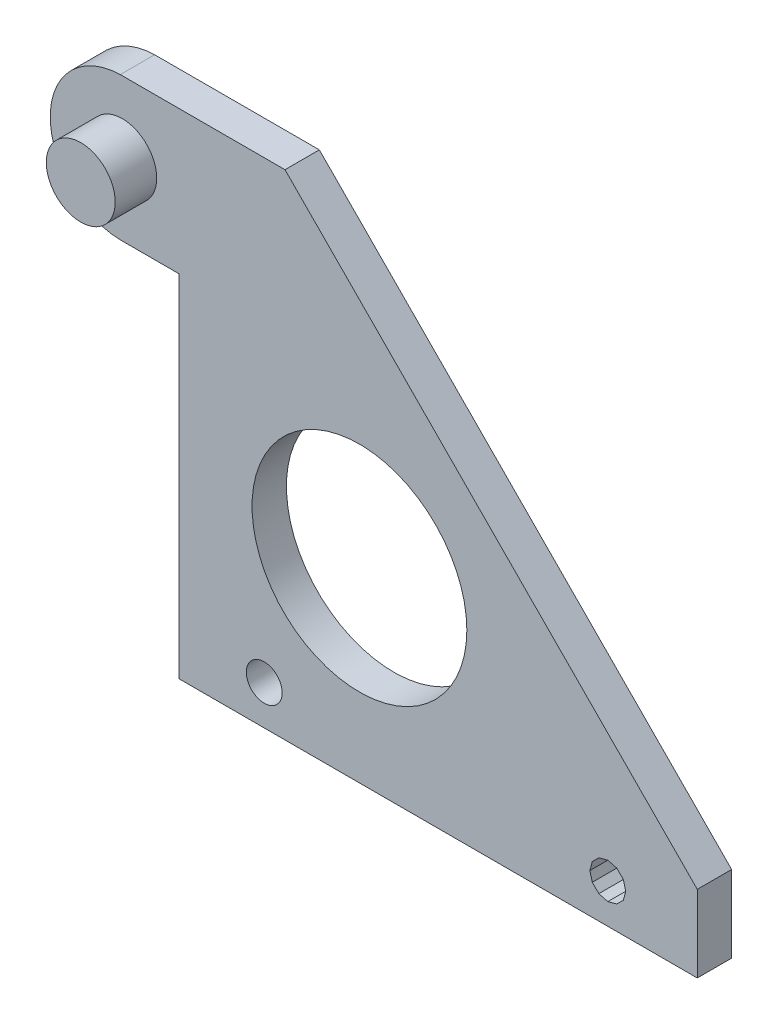
SolidWorks part; units mm, degrees
material "ABS"
ref_plane "Plan de face" through (0, 0, 0) normal (0, 0, 1) x (1, 0, 0)
ref_plane "Plan de dessus" through (0, 0, 0) normal (0, 1, 0) x (1, 0, 0)
ref_plane "Plan de droite" through (0, 0, 0) normal (1, 0, 0) x (0, 0, -1)
ref_plane "Plan1" through (0, 0, 2.4) normal (0, 0, 1) x (1, 0, 0)
sketch "Esquisse4" plane through (0, 0, 2.4) normal (0, 0, 1) x (1, 0, 0)
  line L0 (-20.1, -24.6348) -> (-48.9004, 4.5)
  line L1 (-48.9004, 4.5) -> (-60.4056, 4.5)
  line L2 (-60.4056, 4.5) -> (-61.692, 4.331) construction
  line L3 (-61.692, 4.331) -> (-62.899, 3.831) construction
  line L4 (-62.899, 3.831) -> (-63.935, 3.037) construction
  line L5 (-63.935, 3.037) -> (-64.73, 2.001) construction
  line L6 (-64.73, 2.001) -> (-65.3, 0.625) construction
  line L7 (-65.3, 0.625) -> (-65.3, -1.625) construction
  line L8 (-65.3, -1.625) -> (-64.73, -3.001) construction
  line L9 (-64.73, -3.001) -> (-63.935, -4.037) construction
  line L10 (-63.935, -4.037) -> (-62.899, -4.831) construction
  line L11 (-62.899, -4.831) -> (-61.692, -5.331) construction
  line L12 (-61.692, -5.331) -> (-60.4056, -5.5) construction
  line L13 (-60.4056, -5.5) -> (-56.3, -5.5)
  line L14 (-56.3, -5.5) -> (-56.3, -24.6348)
  line L15 (-56.3, -24.6348) -> (-20.1, -24.6348)
  arc A0 (-60.4056, 4.5) -> (-60.4056, -5.5) centre (-60.2989, -0.5) ccw
extrude "Boss.-Extru.1" add sketch "Esquisse4" against normal blind 2.4
ref_plane "Plan2" through (0, -24.6348, 0) normal (0, -1, 0) x (-1, 0, 0)
sketch "Esquisse9" plane through (0, -24.6348, 0) normal (0, -1, 0) x (-1, 0, 0)
  line L0 (56.3, -2.4) -> (20.1, -2.4)
  line L1 (20.1, -2.4) -> (20.1, 0)
  line L2 (20.1, 0) -> (56.3, 0)
  line L3 (56.3, 0) -> (56.3, -2.4)
extrude "Boss.-Extru.2" add sketch "Esquisse9" along normal blind 5.3652
sketch "Esquisse14" plane through (0, 0, 2.4) normal (0, 0, 1) x (1, 0, 0)
  line L0 (-38.395, -22.305) -> (-37.462, -21.168) construction
  line L1 (-37.462, -21.168) -> (-36.769, -19.871) construction
  line L2 (-36.769, -19.871) -> (-36.342, -18.464) construction
  line L3 (-36.342, -18.464) -> (-36.198, -17) construction
  line L4 (-36.198, -17) -> (-36.7804, -14.9449) construction
  line L5 (-36.7804, -14.9449) -> (-37.2074, -13.5379) construction
  line L6 (-37.2074, -13.5379) -> (-37.9004, -12.2409) construction
  line L7 (-37.9004, -12.2409) -> (-38.3671, -11.6721) construction
  line L8 (-38.3671, -11.6721) -> (-39.532, -10.762) construction
  line L9 (-39.532, -10.762) -> (-40.829, -10.069) construction
  line L10 (-40.829, -10.069) -> (-42.236, -9.642) construction
  line L11 (-42.236, -9.642) -> (-43.7, -9.498) construction
  line L12 (-43.7, -9.498) -> (-45.164, -9.642) construction
  line L13 (-45.164, -9.642) -> (-46.571, -10.069) construction
  line L14 (-46.571, -10.069) -> (-47.868, -10.762) construction
  line L15 (-47.868, -10.762) -> (-49.005, -11.695) construction
  line L16 (-49.005, -11.695) -> (-49.938, -12.832) construction
  line L17 (-49.938, -12.832) -> (-50.631, -14.129) construction
  line L18 (-50.631, -14.129) -> (-51.058, -15.536) construction
  line L19 (-51.058, -15.536) -> (-51.203, -17) construction
  line L20 (-51.203, -17) -> (-51.058, -18.464) construction
  line L21 (-51.058, -18.464) -> (-50.631, -19.871) construction
  line L22 (-50.631, -19.871) -> (-49.938, -21.168) construction
  line L23 (-49.938, -21.168) -> (-49.005, -22.305) construction
  line L24 (-49.005, -22.305) -> (-47.868, -23.238) construction
  line L25 (-47.868, -23.238) -> (-46.571, -23.931) construction
  line L26 (-46.571, -23.931) -> (-45.164, -24.358) construction
  line L27 (-45.164, -24.358) -> (-43.7, -24.502) construction
  line L28 (-43.7, -24.502) -> (-42.236, -24.358) construction
  line L29 (-42.236, -24.358) -> (-40.829, -23.931) construction
  line L30 (-40.829, -23.931) -> (-39.532, -23.238) construction
  line L31 (-39.532, -23.238) -> (-38.395, -22.305) construction
  circle A0 centre (-43.7, -16.9999) radius 7.5023
extrude "Enlèv. mat.-Extru.1" cut sketch "Esquisse14" against normal through all
sketch "Esquisse19" plane through (0, 0, 2.4) normal (0, 0, 1) x (1, 0, 0)
  line L0 (-26.35, -28.503) -> (-25.724, -28.335)
  line L1 (-25.724, -28.335) -> (-25.265, -27.876)
  line L2 (-25.265, -27.876) -> (-25.097, -27.25)
  line L3 (-25.097, -27.25) -> (-25.265, -26.624)
  line L4 (-25.265, -26.624) -> (-25.724, -26.165)
  line L5 (-25.724, -26.165) -> (-26.35, -25.998)
  line L6 (-26.35, -25.998) -> (-26.976, -26.165)
  line L7 (-26.976, -26.165) -> (-27.435, -26.624)
  line L8 (-27.435, -26.624) -> (-27.602, -27.25)
  line L9 (-27.602, -27.25) -> (-27.435, -27.876)
  line L10 (-27.435, -27.876) -> (-26.976, -28.335)
  line L11 (-26.976, -28.335) -> (-26.35, -28.503)
extrude "Enlèv. mat.-Extru.2" cut sketch "Esquisse19" against normal through all
ref_plane "Plan3" through (0, 0, 0) normal (0, 0, -1) x (-1, 0, 0)
sketch "Esquisse25" plane through (0, 0, 0) normal (0, 0, -1) x (-1, 0, 0)
  line L0 (49.265, -26.624) -> (49.097, -27.25) construction
  line L1 (49.097, -27.25) -> (49.265, -27.876) construction
  line L2 (49.265, -27.876) -> (49.724, -28.335) construction
  line L3 (49.724, -28.335) -> (50.35, -28.503) construction
  line L4 (50.35, -28.503) -> (50.976, -28.335) construction
  line L5 (50.976, -28.335) -> (51.435, -27.876) construction
  line L6 (51.435, -27.876) -> (51.602, -27.25) construction
  line L7 (51.602, -27.25) -> (51.2358, -26.3644) construction
  line L8 (51.2358, -26.3644) -> (51.0062, -26.1348) construction
  line L9 (51.0062, -26.1348) -> (50.35, -25.998) construction
  line L10 (50.35, -25.998) -> (49.724, -26.165) construction
  line L11 (49.724, -26.165) -> (49.265, -26.624) construction
  circle A0 centre (50.35, -27.2502) radius 1.2528
extrude "Enlèv. mat.-Extru.3" cut sketch "Esquisse25" against normal through all
sketch "Esquisse28" plane through (0, 0, 2.4) normal (0, 0, 1) x (1, 0, 0)
  circle A0 centre (-60.2677, -0.4991) radius 2.407
extrude "Boss.-Extru.3" add sketch "Esquisse28" along normal blind 2.9
